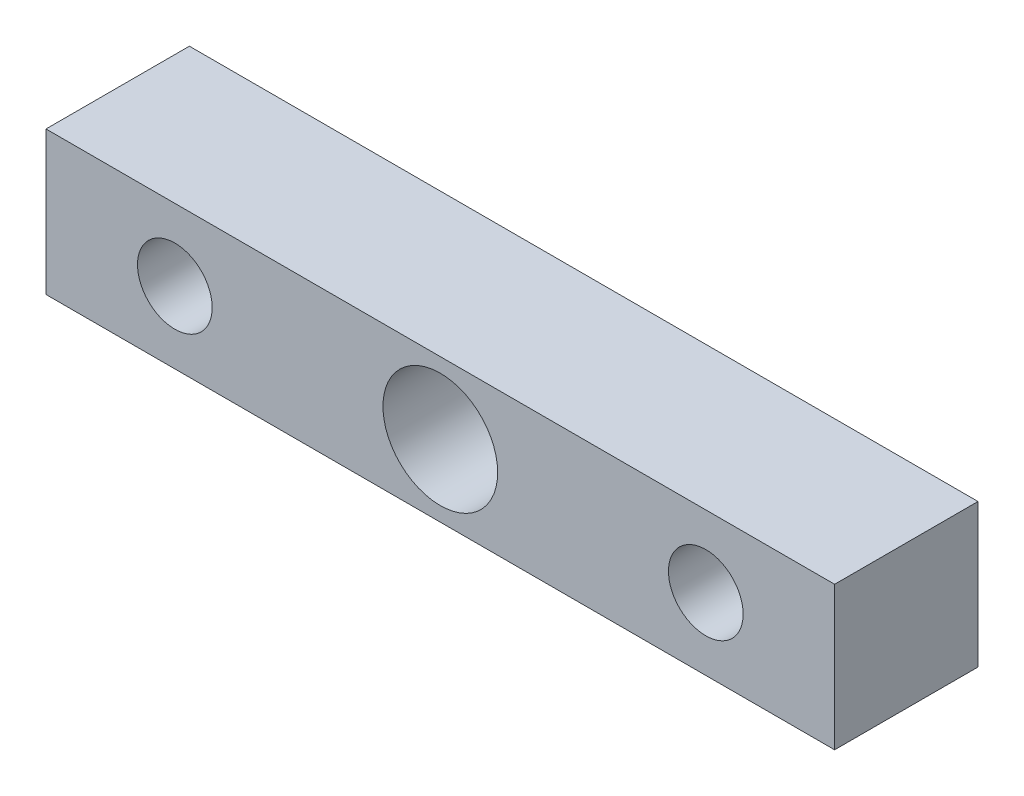
SolidWorks part; units mm, degrees
ref_plane "前视基准面" through (0, 0, 0) normal (0, 0, 1) x (1, 0, 0)
ref_plane "上视基准面" through (0, 0, 0) normal (0, 1, 0) x (1, 0, 0)
ref_plane "右视基准面" through (0, 0, 0) normal (1, 0, 0) x (0, 0, -1)
sketch "草图1" plane through (0, 0, 0) normal (0, 0, 1) x (1, 0, 0)
  line L1 (-27.5, -5) -> (27.5, -5)
  line L2 (-27.5, -5) -> (-27.5, 5)
  line L3 (-27.5, 5) -> (27.5, 5)
  line L4 (27.5, -5) -> (27.5, 5)
  line L5 (-27.5, -5) -> (27.5, 5) construction
  line L6 (-27.5, 5) -> (27.5, -5) construction
  point P0 (0, 0)
  dimension "D1" = 55
  dimension "D2" = 10
extrude "凸台-拉伸1" add sketch "草图1" along normal blind 10
sketch "草图2" plane through (0, 0, 10) normal (0, 0, 1) x (1, 0, 0)
  circle A0 centre (18.515, 0) radius 2.605
  circle A1 centre (-18.515, 0) radius 2.605
  dimension "D1" = 5.21
  dimension "D2" = 5.21
  dimension "D3" = 31.82
  dimension "D4" = 15.91
extrude "切除-拉伸1" cut sketch "草图2" against normal blind 10
sketch "草图3" plane through (0, 0, 10) normal (0, 0, 1) x (1, 0, 0)
  circle A0 centre (0, 0) radius 4
  dimension "D1" = 8
extrude "切除-拉伸2" cut sketch "草图3" against normal blind 10
